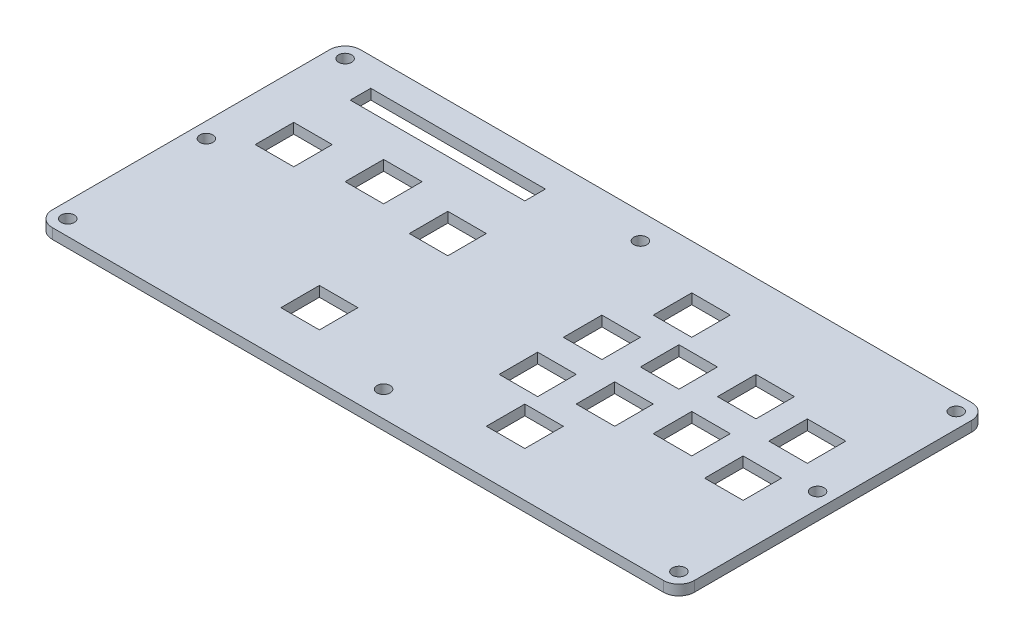
SolidWorks part; units mm, degrees
ref_plane "前视基准面" through (0, 0, 0) normal (0, 0, 1) x (1, 0, 0)
ref_plane "上视基准面" through (0, 0, 0) normal (0, 1, 0) x (1, 0, 0)
ref_plane "右视基准面" through (0, 0, 0) normal (1, 0, 0) x (0, 0, -1)
sketch "草图1" plane through (0, 0, 0) normal (0, 1, 0) x (1, 0, 0)
  line L0 (2958.1534, 1776.764) -> (3196.1534, 1776.764)
  line L1 (3202.1534, 1770.764) -> (3202.1534, 1662.764)
  line L2 (3196.1534, 1656.764) -> (2958.1534, 1656.764)
  line L3 (2952.1534, 1662.764) -> (2952.1534, 1770.764)
  line L4 (2969.6534, 1739.264) -> (2984.6534, 1739.264)
  line L5 (2984.6534, 1739.264) -> (2984.6534, 1724.264)
  line L6 (2984.6534, 1724.264) -> (2969.6534, 1724.264)
  line L7 (2969.6534, 1724.264) -> (2969.6534, 1739.264)
  line L8 (2999.6534, 1744.264) -> (3014.6534, 1744.264)
  line L9 (3014.6534, 1744.264) -> (3014.6534, 1729.264)
  line L10 (3014.6534, 1729.264) -> (2999.6534, 1729.264)
  line L11 (2999.6534, 1729.264) -> (2999.6534, 1744.264)
  line L12 (3094.6534, 1734.264) -> (3109.6534, 1734.264)
  line L13 (3109.6534, 1734.264) -> (3109.6534, 1719.264)
  line L14 (3109.6534, 1719.264) -> (3094.6534, 1719.264)
  line L15 (3094.6534, 1719.264) -> (3094.6534, 1734.264)
  line L16 (3029.6534, 1689.264) -> (3044.6534, 1689.264)
  line L17 (3044.6534, 1689.264) -> (3044.6534, 1674.264)
  line L18 (3044.6534, 1674.264) -> (3029.6534, 1674.264)
  line L19 (3029.6534, 1674.264) -> (3029.6534, 1689.264)
  line L20 (3029.6534, 1739.264) -> (3044.6534, 1739.264)
  line L21 (3044.6534, 1739.264) -> (3044.6534, 1724.264)
  line L22 (3044.6534, 1724.264) -> (3029.6534, 1724.264)
  line L23 (3029.6534, 1724.264) -> (3029.6534, 1739.264)
  line L24 (3104.6534, 1759.264) -> (3119.6534, 1759.264)
  line L25 (3119.6534, 1759.264) -> (3119.6534, 1744.264)
  line L26 (3119.6534, 1744.264) -> (3104.6534, 1744.264)
  line L27 (3104.6534, 1744.264) -> (3104.6534, 1759.264)
  line L28 (3119.6534, 1739.264) -> (3134.6534, 1739.264)
  line L29 (3134.6534, 1739.264) -> (3134.6534, 1724.264)
  line L30 (3134.6534, 1724.264) -> (3119.6534, 1724.264)
  line L31 (3119.6534, 1724.264) -> (3119.6534, 1739.264)
  line L32 (3144.6534, 1744.264) -> (3159.6534, 1744.264)
  line L33 (3159.6534, 1744.264) -> (3159.6534, 1729.264)
  line L34 (3159.6534, 1729.264) -> (3144.6534, 1729.264)
  line L35 (3144.6534, 1729.264) -> (3144.6534, 1744.264)
  line L36 (3119.6534, 1714.264) -> (3134.6534, 1714.264)
  line L37 (3134.6534, 1714.264) -> (3134.6534, 1699.264)
  line L38 (3134.6534, 1699.264) -> (3119.6534, 1699.264)
  line L39 (3119.6534, 1699.264) -> (3119.6534, 1714.264)
  line L40 (3169.6534, 1714.264) -> (3184.6534, 1714.264)
  line L41 (3184.6534, 1714.264) -> (3184.6534, 1699.264)
  line L42 (3184.6534, 1699.264) -> (3169.6534, 1699.264)
  line L43 (3169.6534, 1699.264) -> (3169.6534, 1714.264)
  line L44 (3144.6534, 1719.264) -> (3159.6534, 1719.264)
  line L45 (3159.6534, 1719.264) -> (3159.6534, 1704.264)
  line L46 (3159.6534, 1704.264) -> (3144.6534, 1704.264)
  line L47 (3144.6534, 1704.264) -> (3144.6534, 1719.264)
  line L48 (3094.6534, 1709.264) -> (3109.6534, 1709.264)
  line L49 (3109.6534, 1709.264) -> (3109.6534, 1694.264)
  line L50 (3109.6534, 1694.264) -> (3094.6534, 1694.264)
  line L51 (3094.6534, 1694.264) -> (3094.6534, 1709.264)
  line L52 (3109.6534, 1689.264) -> (3124.6534, 1689.264)
  line L53 (3124.6534, 1689.264) -> (3124.6534, 1674.264)
  line L54 (3124.6534, 1674.264) -> (3109.6534, 1674.264)
  line L55 (3109.6534, 1674.264) -> (3109.6534, 1689.264)
  line L56 (3169.6534, 1739.264) -> (3184.6534, 1739.264)
  line L57 (3184.6534, 1739.264) -> (3184.6534, 1724.264)
  line L58 (3184.6534, 1724.264) -> (3169.6534, 1724.264)
  line L59 (3169.6534, 1724.264) -> (3169.6534, 1739.264)
  line L60 (2973.1534, 1765.764) -> (3041.1534, 1765.764)
  line L61 (3041.1534, 1765.764) -> (3041.1534, 1757.764)
  line L62 (3041.1534, 1757.764) -> (2973.1534, 1757.764)
  line L63 (2973.1534, 1757.764) -> (2973.1534, 1765.764)
  arc A0 (2958.1534, 1776.764) -> (2952.1534, 1770.764) centre (2958.1534, 1770.764) ccw
  arc A1 (3202.1534, 1770.764) -> (3196.1534, 1776.764) centre (3196.1534, 1770.764) ccw
  arc A2 (3196.1534, 1656.764) -> (3202.1534, 1662.764) centre (3196.1534, 1662.764) ccw
  arc A3 (2952.1534, 1662.764) -> (2958.1534, 1656.764) centre (2958.1534, 1662.764) ccw
  circle A4 centre (2958.1534, 1770.764) radius 2.55
  circle A5 centre (3196.1534, 1770.764) radius 2.55
  circle A6 centre (3077.1534, 1766.764) radius 2.55
  circle A7 centre (2958.1534, 1662.764) radius 2.55
  circle A8 centre (3196.1534, 1662.764) radius 2.55
  circle A9 centre (3077.1534, 1666.764) radius 2.55
  circle A10 centre (3196.1534, 1716.764) radius 2.55
  circle A11 centre (2958.1534, 1716.764) radius 2.55
  dimension "D1" = 21
extrude "凸台-拉伸1" add sketch "草图1" along normal blind 4
